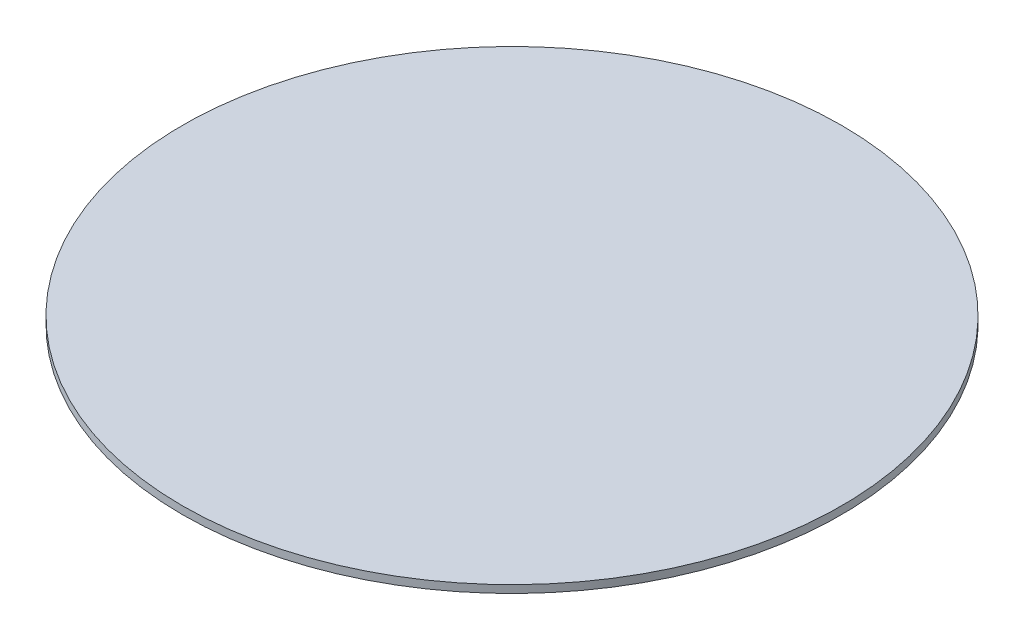
SolidWorks part; units mm, degrees
ref_plane "Front Plane" through (0, 0, 0) normal (0, 0, 1) x (1, 0, 0)
ref_plane "Top Plane" through (0, 0, 0) normal (0, 1, 0) x (1, 0, 0)
ref_plane "Right Plane" through (0, 0, 0) normal (1, 0, 0) x (0, 0, -1)
sketch "Sketch1" plane through (0, 0, 0) normal (0, 1, 0) x (1, 0, 0)
  circle A0 centre (0, 0) radius 76.2
  dimension "D1" = 152.4
extrude "Boss-Extrude1" add sketch "Sketch1" along normal blind 1.778
